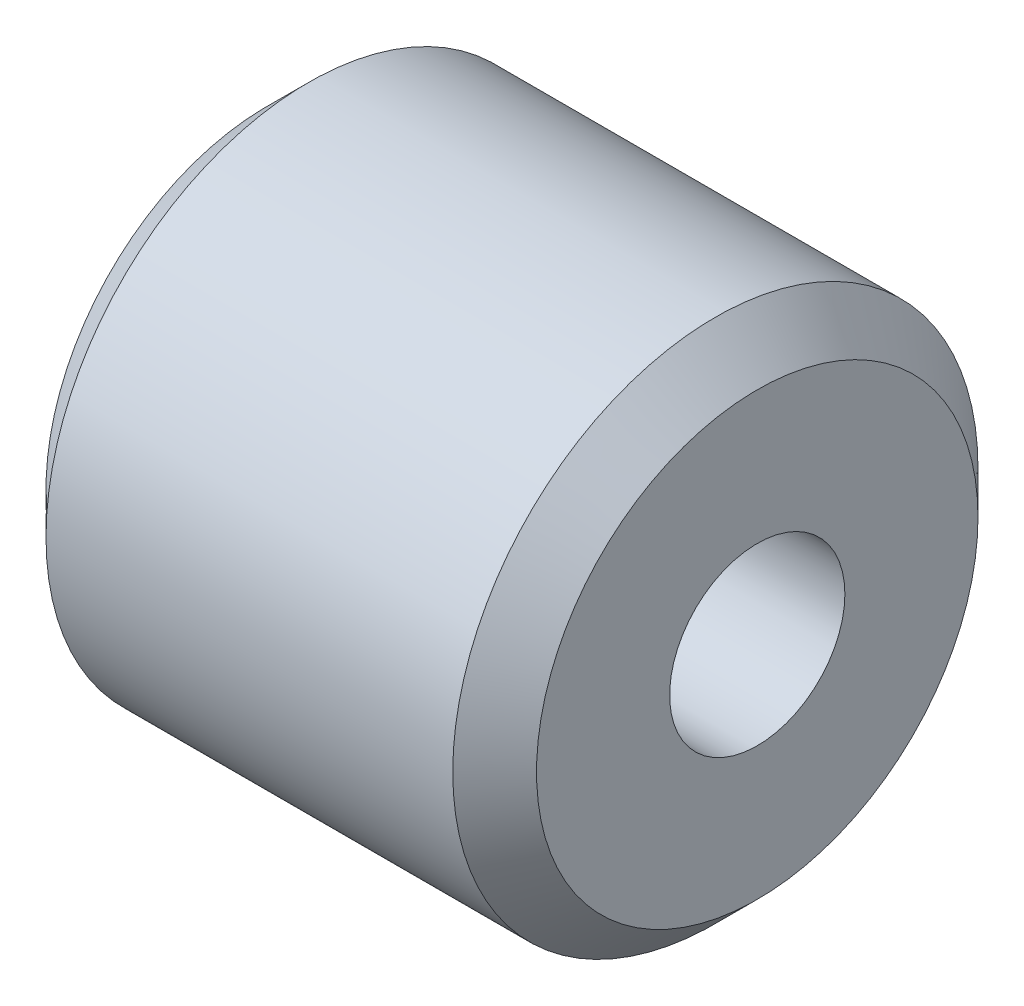
SolidWorks part; units mm, degrees
ref_plane "Front Plane" through (0, 0, 0) normal (0, 0, 1) x (1, 0, 0)
ref_plane "Top Plane" through (0, 0, 0) normal (0, 1, 0) x (1, 0, 0)
ref_plane "Right Plane" through (0, 0, 0) normal (1, 0, 0) x (0, 0, -1)
sketch "Sketch1" plane through (0, 0, 0) normal (1, 0, 0) x (0, 0, -1)
  circle A0 centre (0, 0) radius 1.59
  circle A1 centre (0, 0) radius 4.765
extrude "Boss-Extrude1" add sketch "Sketch1" along normal blind 8.9
chamfer "Chamfer4" distance 0.76 angle 45 2 edges at (0, 0, -4.765) (8.9, 0, -4.765)
